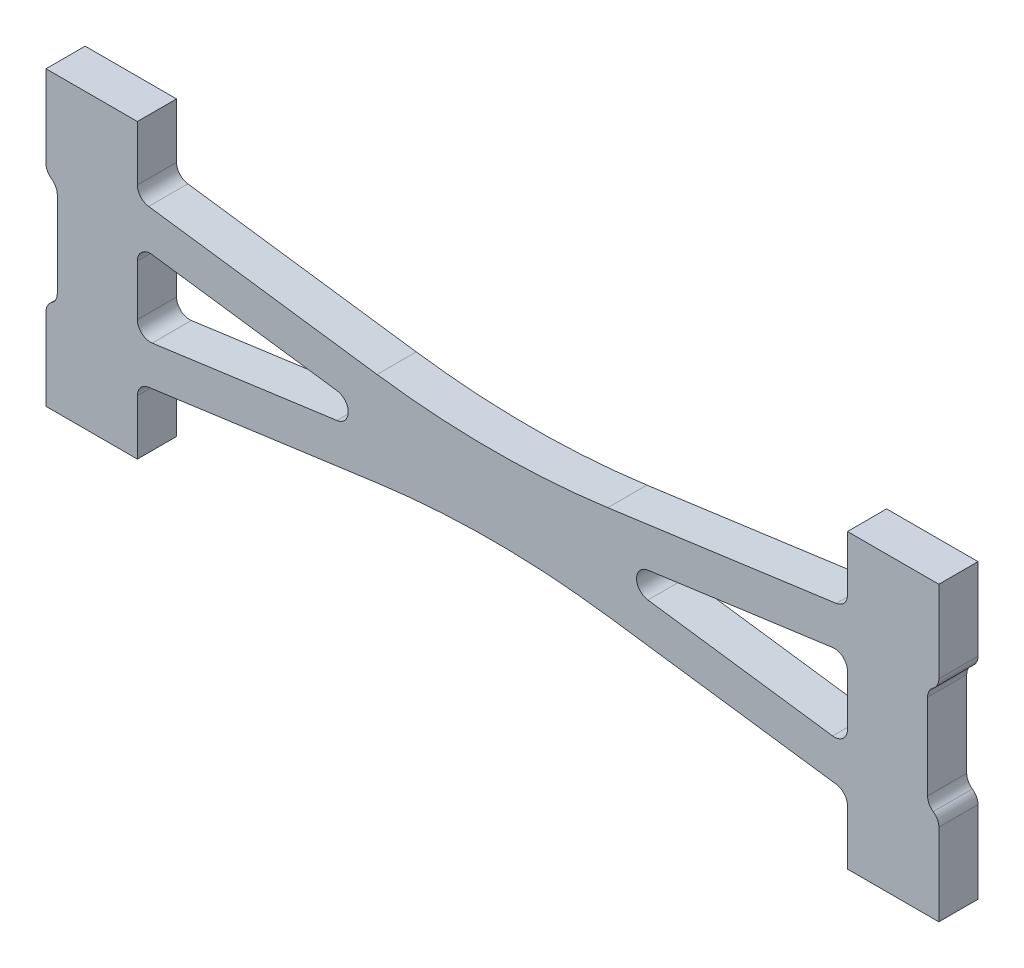
SolidWorks part; units mm, degrees
material "ABS PC"
ref_plane "Front Plane" through (0, 0, 0) normal (0, 0, 1) x (1, 0, 0)
ref_plane "Top Plane" through (0, 0, 0) normal (0, 1, 0) x (1, 0, 0)
ref_plane "Right Plane" through (0, 0, 0) normal (1, 0, 0) x (0, 0, -1)
sketch "Sketch1" plane through (0, 0, 0) normal (0, 0, 1) x (1, 0, 0)
  line L0 (-43.434, -9.779) -> (-43.434, -14.224)
  line L1 (-43.434, -14.224) -> (-34.544, -14.224)
  line L2 (-34.544, -14.224) -> (-34.544, -9.779)
  line L3 (-34.544, -9.779) -> (-34.544, -8.8765)
  line L4 (-43.434, -9.779) -> (-43.434, -6.2507)
  line L5 (-33.1013, -3.7252) -> (-15.1241, -1.2582)
  line L6 (34.544, -2.467) -> (34.544, 2.467)
  line L7 (42.3367, 4.1602) -> (42.3367, -4.1602)
  line L8 (43.434, 9.779) -> (43.434, 14.224)
  line L9 (43.434, 14.224) -> (34.544, 14.224)
  line L10 (0, 3.0285) -> (0, -3.0285) construction
  line L11 (0, -3.0285) -> (0, 3.0285) construction
  line L12 (39.6435, 0) -> (-39.6435, 0) construction
  line L13 (34.544, 14.224) -> (34.544, 9.779)
  line L14 (34.544, 9.779) -> (34.544, 8.8765)
  line L15 (-33.4467, -7.6183) -> (-11.2229, -4.5686)
  line L16 (43.434, 9.779) -> (43.434, 6.2507)
  line L17 (33.1013, 3.7252) -> (15.1241, 1.2582)
  line L18 (-33.4467, 7.6183) -> (-11.2229, 4.5686)
  line L19 (33.4467, 7.6183) -> (11.2229, 4.5686)
  line L20 (33.4467, -7.6183) -> (11.2229, -4.5686)
  line L21 (33.1013, -3.7252) -> (15.1241, -1.2582)
  line L22 (43.434, -9.779) -> (43.434, -6.2507)
  line L23 (34.544, -9.779) -> (34.544, -8.8765)
  line L24 (34.544, -14.224) -> (34.544, -9.779)
  line L25 (-33.1013, 3.7252) -> (-15.1241, 1.2582)
  line L26 (-43.434, 9.779) -> (-43.434, 6.2507)
  line L27 (-34.544, 9.779) -> (-34.544, 8.8765)
  line L28 (-34.544, 14.224) -> (-34.544, 9.779)
  line L29 (-43.434, 14.224) -> (-34.544, 14.224)
  line L30 (-43.434, 9.779) -> (-43.434, 14.224)
  line L31 (-42.3367, 4.1602) -> (-42.3367, -4.1602)
  line L32 (-34.544, -2.467) -> (-34.544, 2.467)
  line L33 (0, 3.8021) -> (0, -3.8021) construction
  line L34 (43.434, -14.224) -> (34.544, -14.224)
  line L35 (43.434, -9.779) -> (43.434, -14.224)
  arc A0 (-34.544, -8.8765) -> (-33.4467, -7.6183) centre (-33.274, -8.8765) cw
  arc A1 (-43.434, -6.2507) -> (-42.8853, -5.2055) centre (-42.164, -6.2507) cw
  arc A2 (34.544, 2.467) -> (33.1013, 3.7252) centre (33.274, 2.467) ccw
  arc A3 (34.544, -2.467) -> (33.1013, -3.7252) centre (33.274, -2.467) cw
  arc A4 (42.3367, -4.1602) -> (42.8853, -5.2055) centre (43.6067, -4.1602) ccw
  arc A5 (42.8853, 5.2055) -> (42.3367, 4.1602) centre (43.6067, 4.1602) ccw
  arc A6 (-43.434, 6.2507) -> (-42.8853, 5.2055) centre (-42.164, 6.2507) ccw
  arc A7 (-34.544, 8.8765) -> (-33.4467, 7.6183) centre (-33.274, 8.8765) ccw
  arc A8 (15.1241, -1.2582) -> (15.1241, 1.2582) centre (15.2968, 0) cw
  arc A9 (-15.1241, -1.2582) -> (-15.1241, 1.2582) centre (-15.2968, 0) ccw
  arc A10 (-11.2229, -4.5686) -> (11.2229, -4.5686) centre (0, -86.3521) cw
  arc A11 (-11.2229, 4.5686) -> (11.2229, 4.5686) centre (0, 86.3521) ccw
  arc A12 (-42.8853, 5.2055) -> (-42.3367, 4.1602) centre (-43.6067, 4.1602) cw
  arc A13 (-42.3367, -4.1602) -> (-42.8853, -5.2055) centre (-43.6067, -4.1602) cw
  arc A14 (-34.544, -2.467) -> (-33.1013, -3.7252) centre (-33.274, -2.467) ccw
  arc A15 (-34.544, 2.467) -> (-33.1013, 3.7252) centre (-33.274, 2.467) cw
  arc A16 (34.544, 8.8765) -> (33.4467, 7.6183) centre (33.274, 8.8765) cw
  arc A17 (43.434, 6.2507) -> (42.8853, 5.2055) centre (42.164, 6.2507) cw
  arc A18 (43.434, -6.2507) -> (42.8853, -5.2055) centre (42.164, -6.2507) ccw
  arc A19 (34.544, -8.8765) -> (33.4467, -7.6183) centre (33.274, -8.8765) ccw
  point P10 (-42.3367, 4.9925)
  point P24 (0, 0)
  point P43 (-42.3367, -4.9925)
  point P57 (5.9554, 0)
  point P60 (-5.9554, 0)
  point P84 (42.3367, -4.9925)
  point P85 (42.3367, 4.9925)
  dimension "D6" = 1.27
  dimension "D8" = 82.55
  dimension "D9" = 1.27
  dimension "D1" = 4.445
  dimension "D2" = 3.81
  dimension "D3" = 8.89
  dimension "D4" = 34.544
  dimension "D5" = 9.779
extrude "Boss-Extrude1" add sketch "Sketch1" along normal blind 3.81
